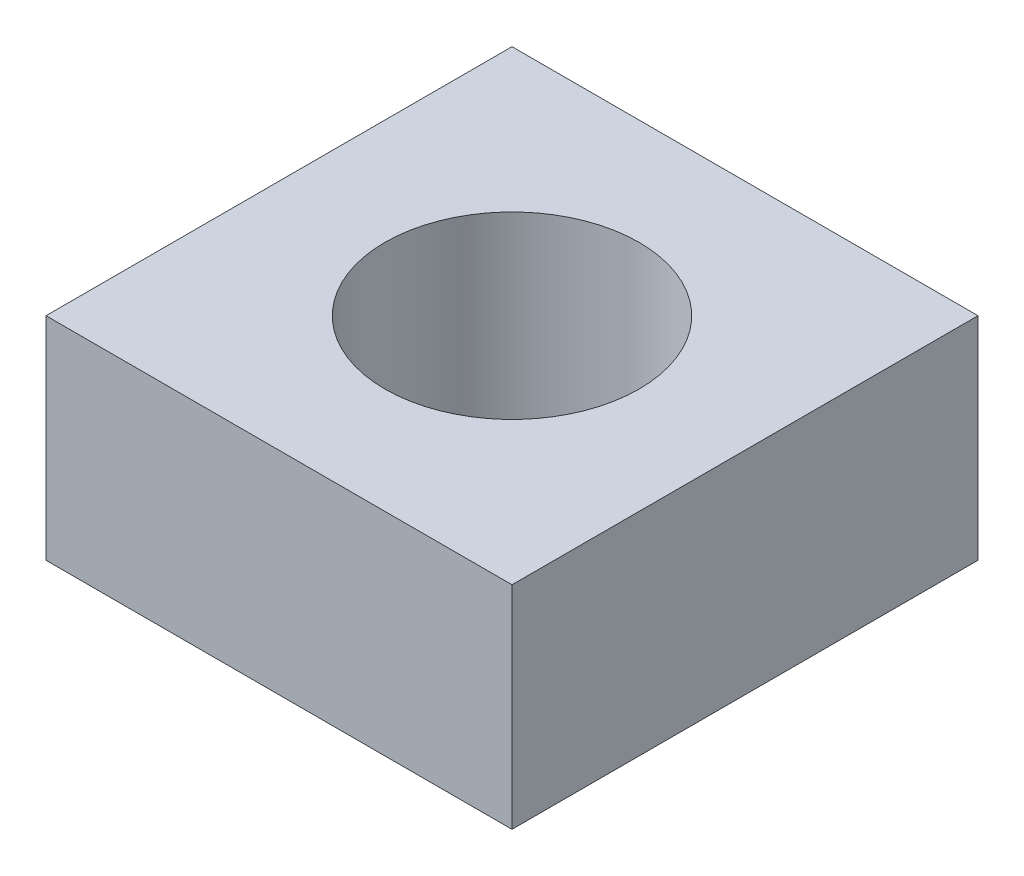
SolidWorks part; units mm, degrees
ref_plane "Front Plane" through (0, 0, 0) normal (0, 0, 1) x (1, 0, 0)
ref_plane "Top Plane" through (0, 0, 0) normal (0, 1, 0) x (1, 0, 0)
ref_plane "Right Plane" through (0, 0, 0) normal (1, 0, 0) x (0, 0, -1)
sketch "Sketch1" plane through (0, 0, 0) normal (0, 1, 0) x (1, 0, 0)
  line L1 (-2.75, -2.75) -> (2.75, -2.75)
  line L2 (-2.75, -2.75) -> (-2.75, 2.75)
  line L3 (-2.75, 2.75) -> (2.75, 2.75)
  line L4 (2.75, -2.75) -> (2.75, 2.75)
  line L5 (-2.75, -2.75) -> (2.75, 2.75) construction
  line L6 (-2.75, 2.75) -> (2.75, -2.75) construction
  circle A0 centre (0, 0) radius 1.5
  point P0 (0, 0)
  dimension "D1" = 5.5
extrude "Boss-Extrude1" add sketch "Sketch1" along normal blind 2.5
